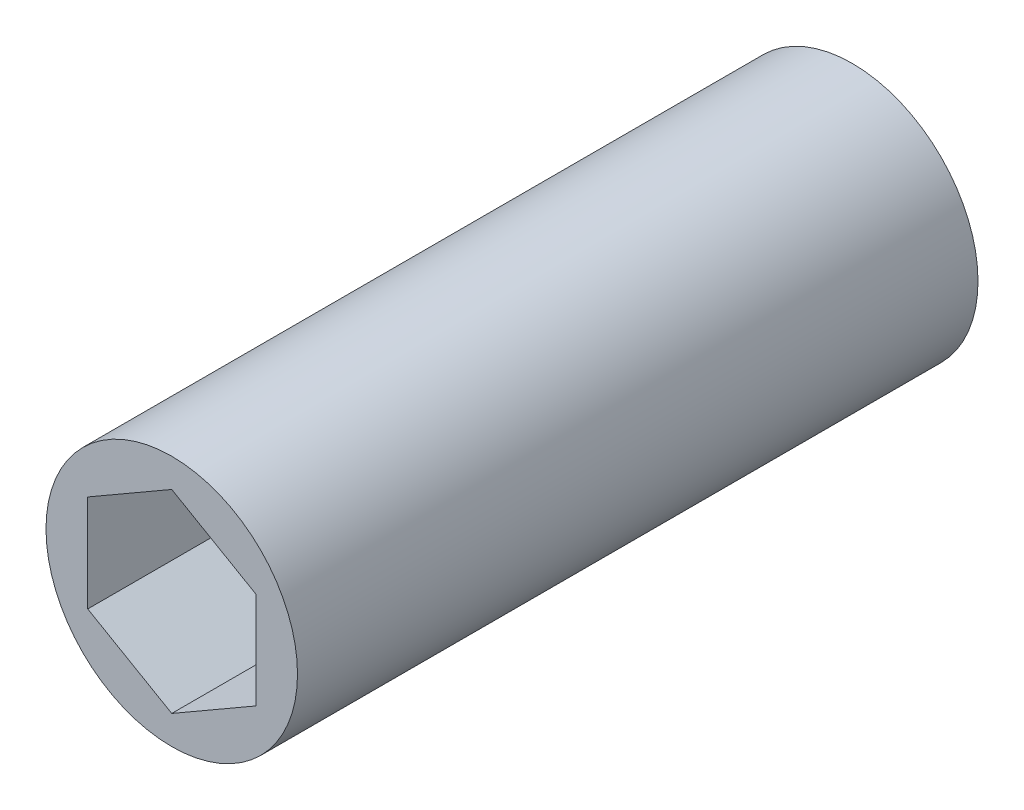
SolidWorks part; units mm, degrees
ref_plane "Front Plane" through (0, 0, 0) normal (0, 0, 1) x (1, 0, 0)
ref_plane "Top Plane" through (0, 0, 0) normal (0, 1, 0) x (1, 0, 0)
ref_plane "Right Plane" through (0, 0, 0) normal (1, 0, 0) x (0, 0, -1)
sketch "Sketch1" plane through (0, 0, 0) normal (0, 0, 1) x (1, 0, 0)
  line L1 (6.3627, 3.6735) -> (0, 7.347)
  line L2 (0, 7.347) -> (-6.3627, 3.6735)
  line L3 (-6.3627, 3.6735) -> (-6.3627, -3.6735)
  line L4 (-6.3627, -3.6735) -> (0, -7.347)
  line L5 (0, -7.347) -> (6.3627, -3.6735)
  line L6 (6.3627, -3.6735) -> (6.3627, 3.6735)
  circle A0 centre (0, 0) radius 6.3627 construction
  circle A1 centre (0, 0) radius 9.525
  dimension "D1" = 12.7254
  dimension "D2" = 19.05
extrude "Boss-Extrude1" add sketch "Sketch1" along normal mid plane 51.5445
